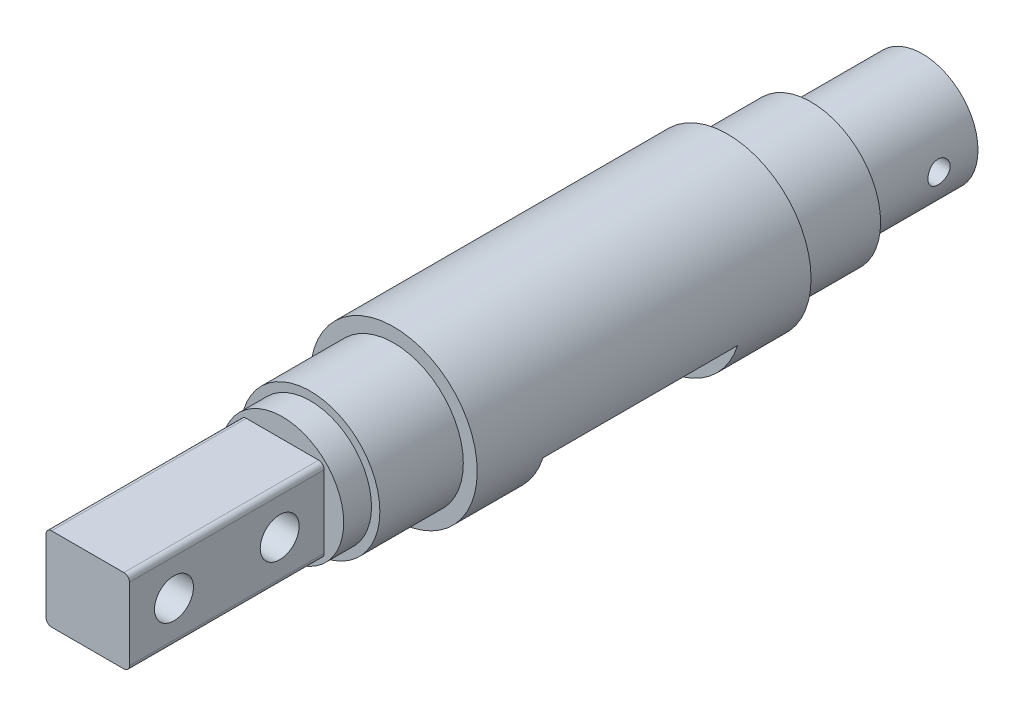
SolidWorks part; units mm, degrees
material "AISI 1045 钢，冷拔"
ref_plane "前视" through (0, 0, 0) normal (0, 0, 1) x (1, 0, 0)
ref_plane "上视" through (0, 0, 0) normal (0, 1, 0) x (1, 0, 0)
ref_plane "右视" through (0, 0, 0) normal (1, 0, 0) x (0, 0, -1)
sketch "草图1" plane through (0, 0, 0) normal (0, 0, 1) x (1, 0, 0)
  circle A0 centre (0, 0) radius 10
  dimension "D1" = 20
extrude "凸台-拉伸1" add sketch "草图1" along normal blind 20
sketch "草图2" plane through (0, 0, 20) normal (0, 0, 1) x (1, 0, 0)
  circle A0 centre (0, 0) radius 12.5
  dimension "D1" = 25
extrude "凸台-拉伸2" add sketch "草图2" along normal blind 15
sketch "草图3" plane through (0, 0, 35) normal (0, 0, 1) x (1, 0, 0)
  circle A0 centre (0, 0) radius 15
  dimension "D1" = 30
extrude "凸台-拉伸3" add sketch "草图3" along normal blind 60
sketch "草图4" plane through (0, 0, 95) normal (0, 0, 1) x (1, 0, 0)
  circle A0 centre (0, 0) radius 12.5
  dimension "D1" = 25
extrude "凸台-拉伸4" add sketch "草图4" along normal blind 15
sketch "草图5" plane through (0, 0, 110) normal (0, 0, 1) x (1, 0, 0)
  circle A0 centre (0, 0) radius 11
  dimension "D1" = 22
extrude "凸台-拉伸5" add sketch "草图5" along normal blind 5
sketch "草图6" plane through (0, 0, 115) normal (0, 0, 1) x (1, 0, 0)
  line L1 (7.5, -7.5) -> (-7.5, -7.5)
  line L2 (7.5, -7.5) -> (7.5, 7.5)
  line L3 (7.5, 7.5) -> (-7.5, 7.5)
  line L4 (-7.5, -7.5) -> (-7.5, 7.5)
  line L5 (-35.3175, -8.351) -> (-26.5284, -14.1155) construction
  line L6 (7.5, -7.5) -> (-7.5, 7.5) construction
  line L7 (7.5, 7.5) -> (-7.5, -7.5) construction
  point P0 (0, 0)
  dimension "D1" = 15
  dimension "D2" = 15
extrude "凸台-拉伸6" add sketch "草图6" along normal blind 35
sketch "草图7" plane through (0, 0, 0) normal (0, 0, -1) x (-1, 0, 0)
  circle A0 centre (0, 0) radius 3
  dimension "D1" = 6
extrude "切除-拉伸1" cut sketch "草图7" against normal blind 20
sketch "草图8" plane through (0, 0, 0) normal (1, 0, 0) x (0, 0, -1)
  line L0 (0, -10) -> (0, 10) construction
  circle A0 centre (-7, 0) radius 2
  point P2 (0, 0)
  dimension "D1" = 4
  dimension "D2" = 7
extrude "切除-拉伸2" cut sketch "草图8" against normal mid plane 40
sketch "草图9" plane through (0, 0, 0) normal (1, 0, 0) x (0, 0, -1)
  line L0 (-95, -15) -> (-35, -15) construction
  line L1 (-82.5, -4.5) -> (-47.5, -4.5)
  line L2 (-82.5, -4.5) -> (-82.5, -15)
  line L3 (-82.5, -15) -> (-47.5, -15)
  line L4 (-47.5, -4.5) -> (-47.5, -15)
  line L5 (-95, 12.5) -> (-95, -12.5) construction
  dimension "D1" = 10.5
  dimension "D2" = 35
  dimension "D3" = 12.5
extrude "切除-拉伸3" cut sketch "草图9" against normal mid plane 40
sketch "草图10" plane through (0, 0, 0) normal (1, 0, 0) x (0, 0, -1)
  line L2 (-170.5231, 0) -> (-100.8029, 0) construction
  line L3 (-150, -7.5) -> (-150, 7.5) construction
  line L4 (-115, -7.5) -> (-115, 7.5) construction
  circle A0 centre (-142, 0) radius 3.5
  circle A1 centre (-123, 0) radius 3.5
  dimension "D1" = 7
  dimension "D2" = 7
  dimension "D3" = 8
  dimension "D4" = 8
extrude "切除-拉伸4" cut sketch "草图10" against normal mid plane 40
fillet "圆角1" radius 1 4 edges at (-7.5, -7.5, 132.5) (7.5, -7.5, 132.5) (-7.5, 7.5, 132.5) (7.5, 7.5, 132.5)
